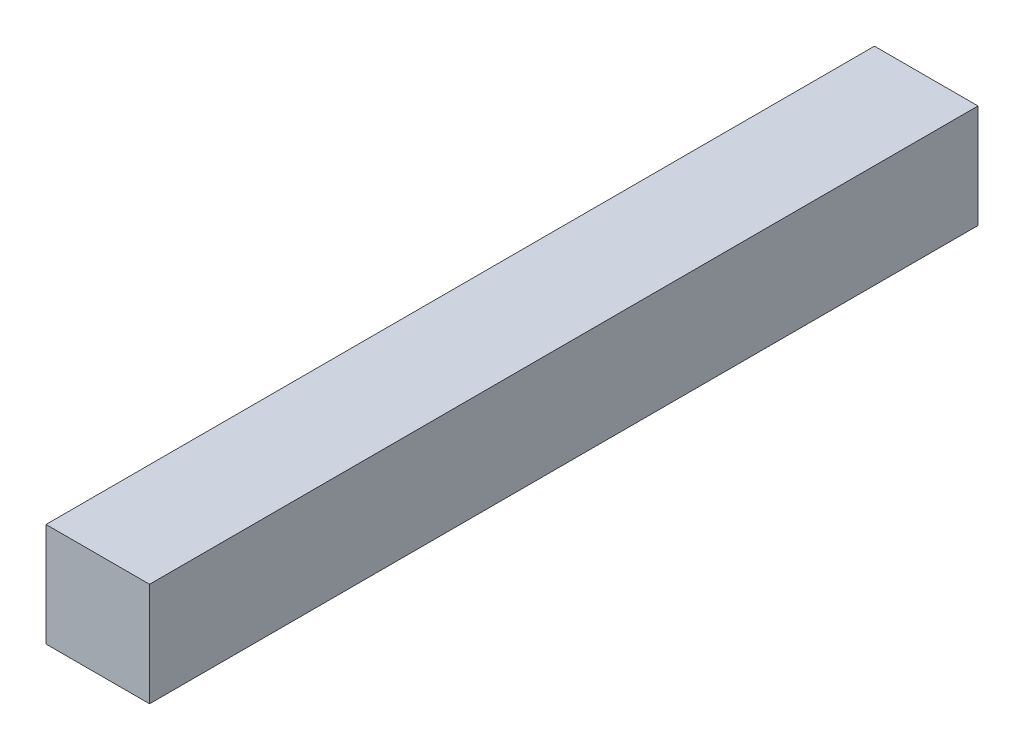
SolidWorks part; units mm, degrees
ref_plane "Front Plane" through (0, 0, 0) normal (0, 0, 1) x (1, 0, 0)
ref_plane "Top Plane" through (0, 0, 0) normal (0, 1, 0) x (1, 0, 0)
ref_plane "Right Plane" through (0, 0, 0) normal (1, 0, 0) x (0, 0, -1)
sketch "Sketch2" plane through (0, 0, 0) normal (0, 0, 1) x (1, 0, 0)
  line L1 (0, 0) -> (5, 0)
  line L2 (0, 0) -> (0, 5)
  line L3 (0, 5) -> (5, 5)
  line L4 (5, 0) -> (5, 5)
  dimension "D1" = 5
  dimension "D2" = 5
extrude "Boss-Extrude1" add sketch "Sketch2" against normal blind 40
